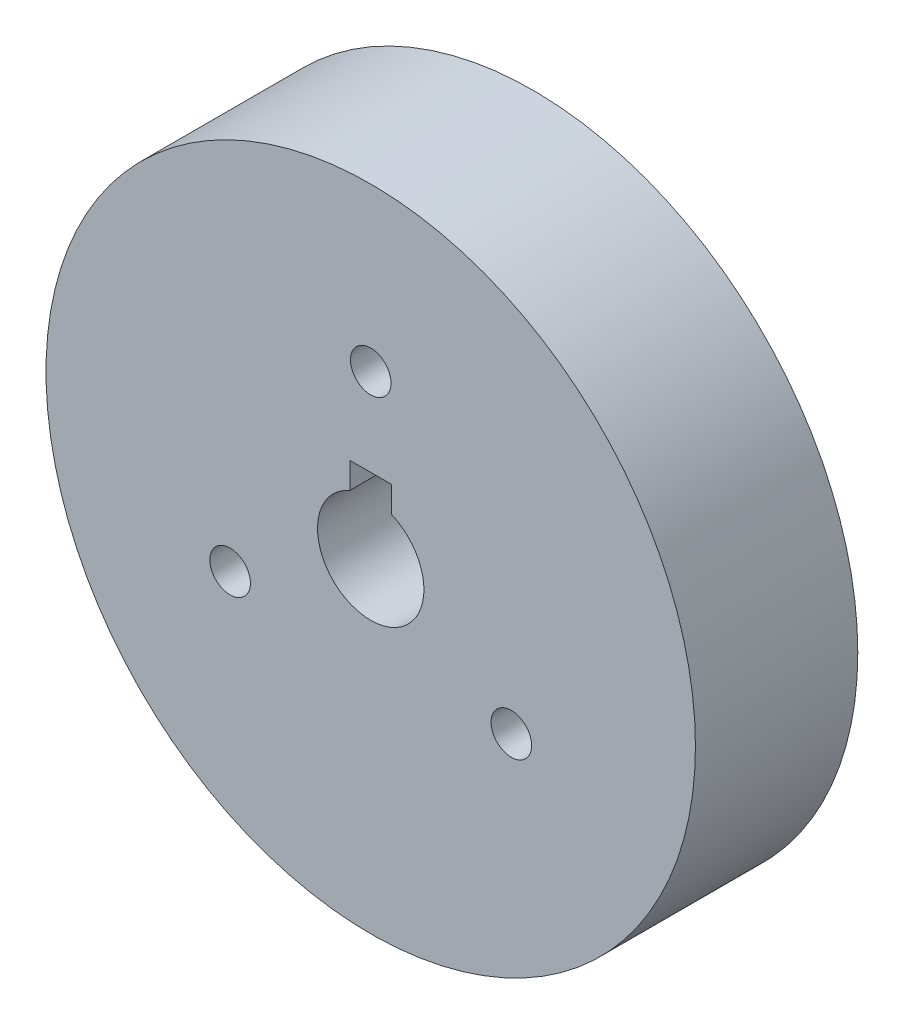
SolidWorks part; units mm, degrees
ref_plane "Front Plane" through (0, 0, 0) normal (0, 0, 1) x (1, 0, 0)
ref_plane "Top Plane" through (0, 0, 0) normal (0, 1, 0) x (1, 0, 0)
ref_plane "Right Plane" through (0, 0, 0) normal (1, 0, 0) x (0, 0, -1)
sketch "Sketch1" plane through (0, 0, 0) normal (0, 0, 1) x (1, 0, 0)
  circle A1 centre (0, 0) radius 20
  circle A6 centre (0, 0) radius 10 construction
  circle A7 centre (0, 10) radius 1.2505
  circle A8 centre (0, 0) radius 3.275
  circle A9 centre (8.6603, -5) radius 1.2505
  circle A10 centre (-8.6603, -5) radius 1.2505
  point P9 (0, 0)
  dimension "D1" = 20
  dimension "D2" = 40
  dimension "D3" = 6.55
  dimension "D4" = 2.501
  dimension "D5" = 3
extrude "Boss-Extrude1" add sketch "Sketch1" along normal blind 10
sketch "Sketch2" plane through (0, 0, 10) normal (0, 0, 1) x (1, 0, 0)
  line L0 (-1.2906, 1.9844) -> (1.2906, 1.9844) construction
  line L1 (-1.2906, 0) -> (1.2906, 0)
  line L2 (-1.2906, 0) -> (-1.2906, 4.6156)
  line L3 (-1.2906, 4.6156) -> (1.2906, 4.6156)
  line L4 (1.2906, 0) -> (1.2906, 4.6156)
  circle A0 centre (0, 0) radius 3.275 construction
  point P4 (0, 0)
  dimension "D1" = 2.5813
  dimension "D2" = 1.2906
  dimension "D3" = 2.6312
extrude "Cut-Extrude1" cut sketch "Sketch2" against normal through all both and the other way through all
equation "\"D3@Sketch1\"=0.25in+0.2mm"
equation "\"D1@Sketch2\"=0.09375in+0.2mm"
equation "\"D2@Sketch2\"=0.046875in+0.1mm"
equation "\"D3@Sketch2\"=\"D1@Sketch2\"+0.05mm"
